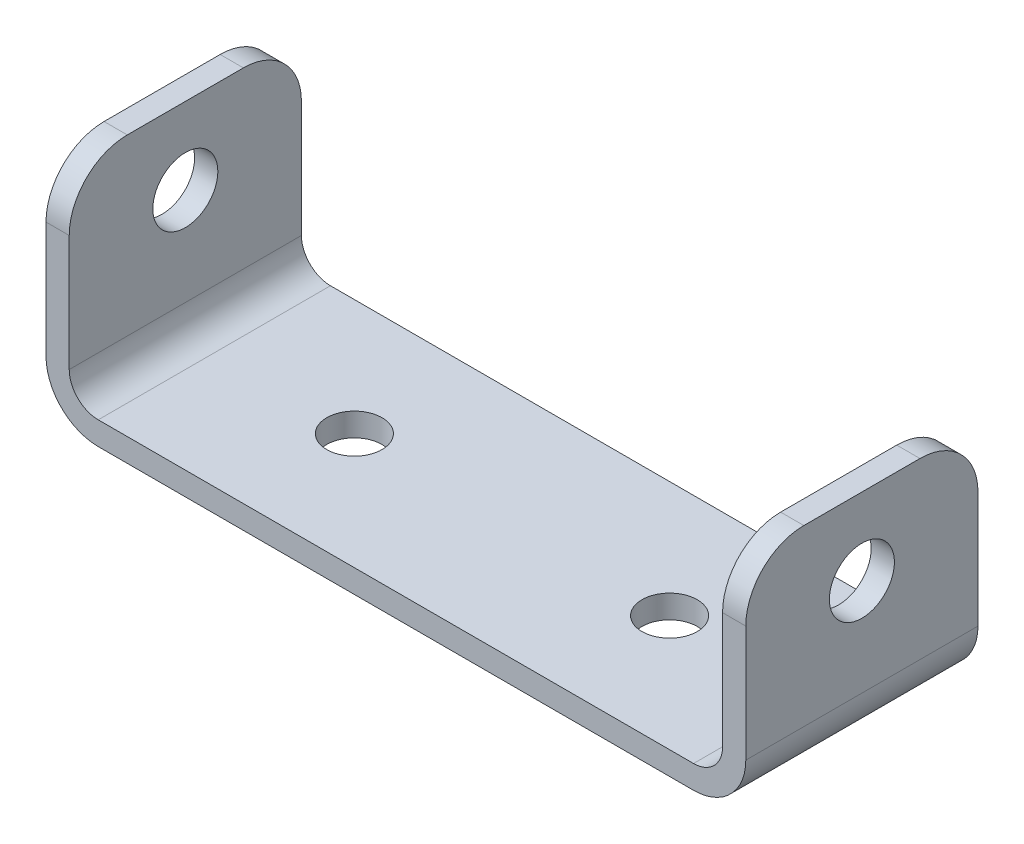
SolidWorks part; units mm, degrees
ref_plane "Front Plane" through (0, 0, 0) normal (0, 0, 1) x (1, 0, 0)
ref_plane "Top Plane" through (0, 0, 0) normal (0, 1, 0) x (1, 0, 0)
ref_plane "Right Plane" through (0, 0, 0) normal (1, 0, 0) x (0, 0, -1)
sketch "Sketch1" plane through (0, 0, 0) normal (0, 0, 1) x (1, 0, 0)
  line L0 (0, 22.225) -> (0, 3.175)
  line L1 (3.175, 0) -> (68.2907, 0)
  line L2 (71.4657, 3.175) -> (71.4657, 22.225)
  arc A0 (68.2907, 0) -> (71.4657, 3.175) centre (68.2907, 3.175) ccw
  arc A1 (0, 3.175) -> (3.175, 0) centre (3.175, 3.175) ccw
  point P9 (0, 0)
  dimension "D1" = 3.175
  dimension "tab length" = 19.05
extrude "Extrude-Thin1" add sketch "Sketch1" along normal blind 25.4 thin
sketch "Sketch3" plane through (0, 0, 0) normal (0, 1, 0) x (1, 0, 0)
  line L0 (3.175, -12.7) -> (68.2907, -12.7) construction
  line L1 (3.175, -25.4) -> (3.175, 0) construction
  line L2 (68.2907, -25.4) -> (68.2907, 0) construction
  line L3 (35.7329, -12.7) -> (35.7329, -1.6671) construction
  line L4 (18.4933, -15.8368) -> (18.4933, -4.7494) construction
  circle A0 centre (18.4933, -12.7) radius 3.022
  circle A1 centre (52.9725, -12.7) radius 3.022
extrude "Extrude2" cut sketch "Sketch3" against normal through all
sketch "Sketch4" plane through (0, 0, 0) normal (1, 0, 0) x (0, 0, -1)
  line L0 (-12.7, 22.225) -> (-12.7, 13.8219) construction
  line L1 (-25.4, 22.225) -> (0, 22.225) construction
  circle A0 centre (-12.7, 13.8219) radius 3.556
  dimension "D1" = 7.112
  dimension "D2" = 8.4031
extrude "Extrude3" cut sketch "Sketch4" against normal mid plane 163.068
fillet "Fillet1" radius 6.35 4 edges at (72.7357, 22.225, 0) (72.7357, 22.225, 25.4) (-1.27, 22.225, 0) (-1.27, 22.225, 25.4)
ref_plane "Plane2" [suppressed] through (0, 22.225, 0) normal (0, 1, 0) x (-1, 0, 0)
sketch "Sketch5" [suppressed] plane through (0, 22.225, 0) normal (0, 1, 0) x (-1, 0, 0)
  line L0 (0, 12.7) -> (-71.4657, 12.7) construction
  line L1 (0, 0) -> (24.6464, 0)
  line L2 (0, 0) -> (0, 25.4)
  line L3 (0, 25.4) -> (24.6464, 25.4)
  line L4 (27.8214, 3.175) -> (27.8214, 22.225)
  line L5 (-71.4657, 25.4) -> (-71.4657, 0) construction
  line L6 (-35.7329, 12.7) -> (-35.7329, -12.8035) construction
  line L7 (-99.2872, 3.175) -> (-99.2872, 22.225)
  line L8 (-71.4657, 25.4) -> (-96.1122, 25.4)
  line L9 (-71.4657, 0) -> (-71.4657, 25.4)
  line L10 (-71.4657, 0) -> (-96.1122, 0)
  arc A0 (24.6464, 0) -> (27.8214, 3.175) centre (24.6464, 3.175) ccw
  arc A1 (24.6464, 25.4) -> (27.8214, 22.225) centre (24.6464, 22.225) cw
  arc A2 (-96.1122, 25.4) -> (-99.2872, 22.225) centre (-96.1122, 22.225) ccw
  arc A3 (-96.1122, 0) -> (-99.2872, 3.175) centre (-96.1122, 3.175) cw
  dimension "D1" = 3.175
extrude "Extrude4" [suppressed] add sketch "Sketch5" along normal blind 3.175
sketch "Sketch6" [suppressed] plane through (0, 22.225, 0) normal (0, 1, 0) x (-1, 0, 0)
  line L0 (0, 12.7) -> (14.7403, 12.7) construction
  line L1 (0, 25.4) -> (0, 0) construction
  line L2 (0, 12.7) -> (-71.181, 12.7) construction
  line L3 (-35.5905, 12.7) -> (-35.5905, -11.4577) construction
  circle A0 centre (14.7403, 12.7) radius 3.175
  circle A1 centre (-85.9213, 12.7) radius 3.175
  dimension "D1" = 6.35
extrude "Extrude5" [suppressed] cut sketch "Sketch6" along normal blind 19.939
